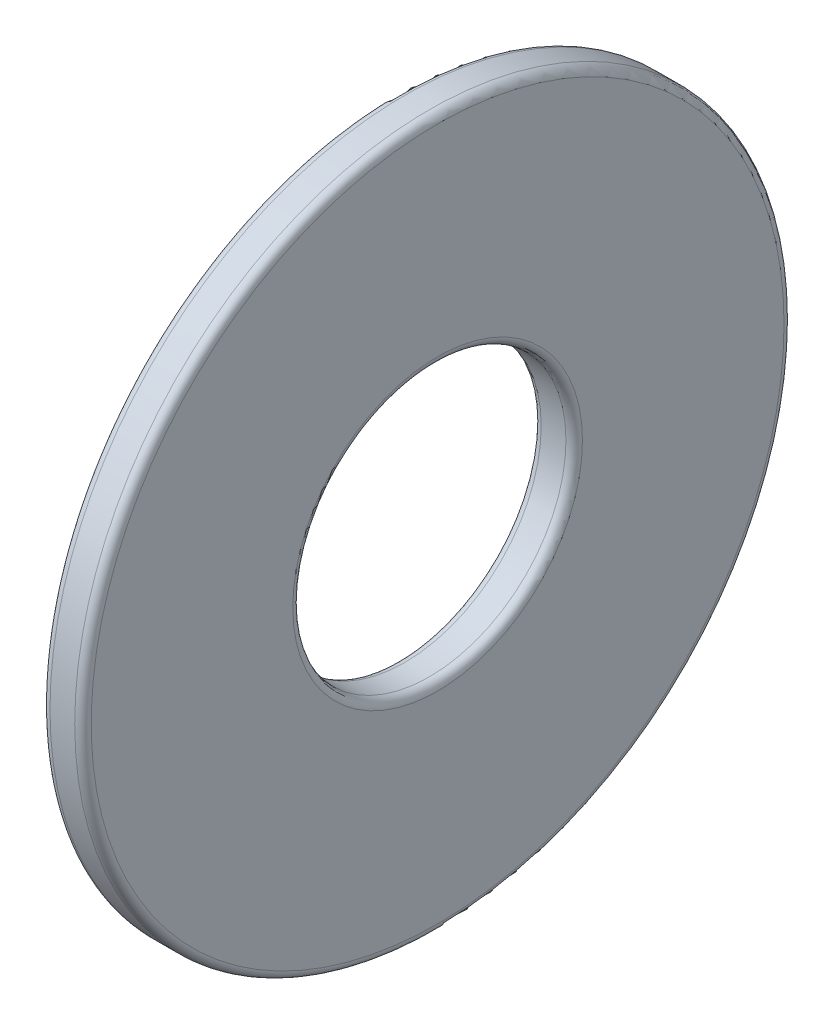
SolidWorks part; units mm, degrees
ref_plane "Front Plane" through (0, 0, 0) normal (0, 0, 1) x (1, 0, 0)
ref_plane "Top Plane" through (0, 0, 0) normal (0, 1, 0) x (1, 0, 0)
ref_plane "Right Plane" through (0, 0, 0) normal (1, 0, 0) x (0, 0, -1)
sketch "Sketch3" plane through (0, 0, 0) normal (0, 0, 1) x (1, 0, 0)
  line L0 (-0.508, 0) -> (0.508, 0) construction
  line L1 (0, -8.7376) -> (0, 8.7376) construction
  line L2 (0, -3.3655) -> (0, 3.3655) construction
  line L4 (0.508, -8.7376) -> (-0.508, -8.7376)
  line L5 (0.508, -8.7376) -> (0.508, 8.7376)
  line L6 (0.508, 8.7376) -> (-0.508, 8.7376)
  line L7 (-0.508, -8.7376) -> (-0.508, 8.7376)
  line L8 (0, 8.7376) -> (0, -8.7376) construction
  line L9 (0.508, 0) -> (-0.508, 0) construction
  point P0 (0, 0)
  point P4 (0, 0)
  point P8 (0, 0)
  point P11 (0, 0)
  dimension "ID" = 6.731
  dimension "OD" = 17.4752
  dimension "Thickness" = 1.016
sketch "Sketch1" plane through (0, 0, 0) normal (1, 0, 0) x (0, 0, -1)
  circle A0 centre (0, 0) radius 8.7376
  circle A1 centre (0, 0) radius 3.3655
extrude "Boss-Extrude1" add sketch "Sketch1" along normal mid plane 1.016
fillet "Fillet1" radius 0.2032 4 edges at (0.508, 0, -8.7376) (-0.508, 0, -8.7376) (0.508, 0, -3.3655) (-0.508, 0, -3.3655)
sketch "Sketch4" plane through (-0.508, 0, 0) normal (-1, 0, 0) x (0, 0, 1)
  line L0 (0, -8.7376) -> (0, 8.7376) construction
  line L1 (0, -8.7376) -> (0, 8.7376) construction
  circle A0 centre (0, 0) radius 3.3655 construction
  circle A1 centre (0, 0) radius 8.7376 construction
  circle A2 centre (0, 0) radius 3.3655 construction
  circle A3 centre (0, 0) radius 8.7376 construction
  point P0 (0, -3.3655)
  point P1 (0, 3.3655)
  point P5 (-8.7376, 0)
  point P9 (-3.3655, 0)
  point P10 (3.3655, 0)
  point P11 (8.7376, 0)
equation "\"D1@Boss-Extrude1\" = \"Thickness@Sketch3\""
equation "\"D1@Fillet1\"=\"Thickness@Sketch3\"*.2"
